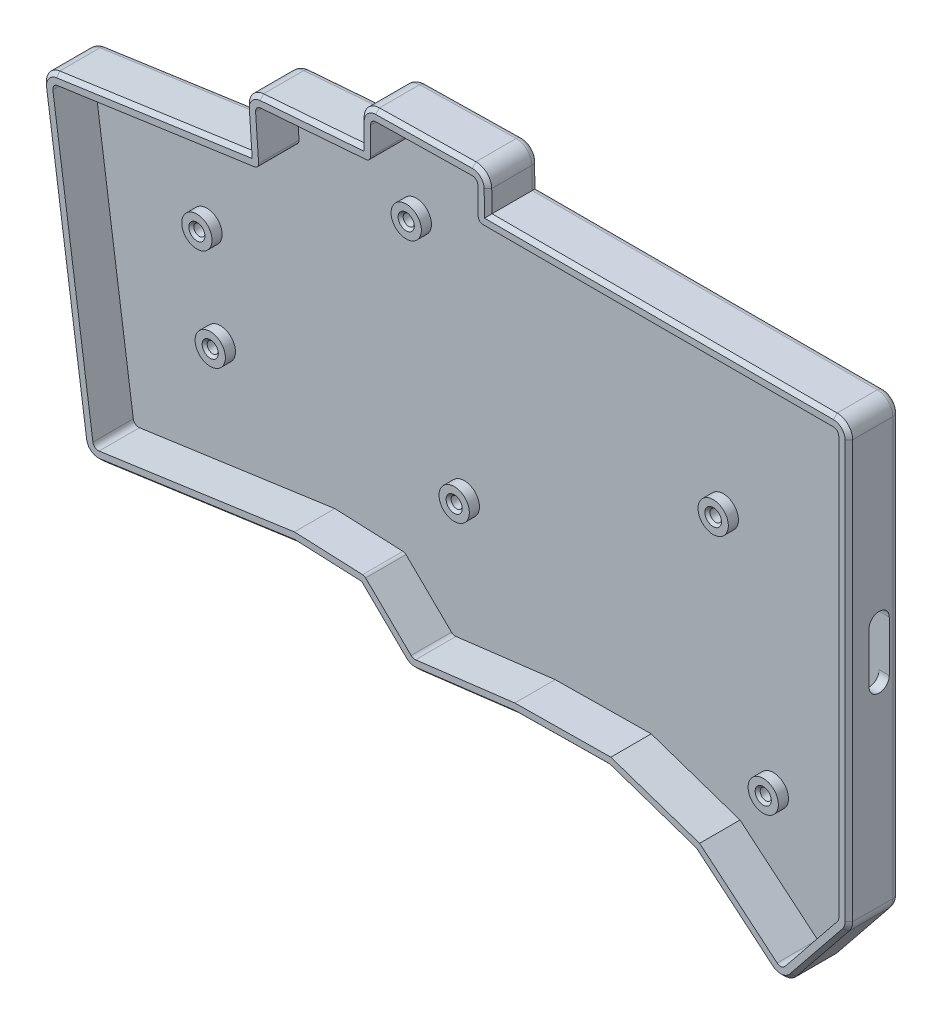
SolidWorks part; units mm, degrees
ref_plane "Front Plane" through (0, 0, 0) normal (0, 0, 1) x (1, 0, 0)
ref_plane "Top Plane" through (0, 0, 0) normal (0, 1, 0) x (1, 0, 0)
ref_plane "Right Plane" through (0, 0, 0) normal (1, 0, 0) x (0, 0, -1)
sketch "Sketch3" plane through (0, 0, 0) normal (0, 0, 1) x (1, 0, 0)
  line L0 (85.1833, 97.7805) -> (154.5968, 97.7805)
  line L1 (155.6718, 96.7055) -> (155.6718, 14.0578)
  line L2 (155.4344, 13.384) -> (144.9894, 0.4011)
  line L3 (143.4619, 0.2505) -> (128.1082, 13.0973)
  line L4 (128.1082, 13.0973) -> (143.4619, 0.2505)
  line L5 (128.1082, 13.0973) -> (110.5249, 19.0829)
  line L6 (110.5249, 19.0829) -> (91.5019, 18.8692)
  line L7 (91.5019, 18.8692) -> (71.8411, 16.4484)
  line L8 (70.9583, 16.7466) -> (61.9589, 25.5411)
  line L9 (70.9583, 16.7466) -> (61.9589, 25.5411)
  line L10 (61.3523, 25.8037) -> (47.8521, 26.3837)
  line L11 (47.8521, 26.3837) -> (9.158, 20.9127)
  line L12 (7.9428, 21.8276) -> (0.0098, 78.274)
  line L13 (0.9224, 79.4879) -> (39.9728, 85.0637)
  line L14 (40.7648, 86.0439) -> (40.1665, 94.5997)
  line L15 (41.1563, 95.7465) -> (62.0679, 97.3591)
  line L16 (62.9218, 98.2813) -> (62.9218, 103.7219)
  line L17 (63.979, 104.7967) -> (83.0927, 105.1138)
  line L18 (84.1855, 104.0536) -> (84.2584, 98.6929)
  line L19 (61.2805, 24.8059) -> (47.901, 25.3807)
  line L20 (47.901, 25.3807) -> (9.298, 19.9225)
  line L21 (6.9525, 21.6885) -> (-0.9804, 78.1349)
  line L22 (0.7811, 80.4778) -> (39.7624, 86.0438)
  line L23 (39.7624, 86.0438) -> (39.169, 94.5299)
  line L24 (41.0794, 96.7436) -> (61.9218, 98.3508)
  line L25 (61.9218, 98.3508) -> (61.9218, 103.7219)
  line L26 (63.9624, 105.7966) -> (83.0761, 106.1137)
  line L27 (85.1854, 104.0671) -> (85.2573, 98.7805)
  line L28 (85.2573, 98.7805) -> (154.5968, 98.7805)
  line L29 (156.6718, 96.7055) -> (156.6718, 14.0578)
  line L30 (156.2136, 12.7572) -> (145.7685, -0.2258)
  line L31 (142.8202, -0.5165) -> (127.6095, 12.2107)
  line L32 (127.6095, 12.2107) -> (110.3649, 18.081)
  line L33 (110.3649, 18.081) -> (91.5689, 17.8699)
  line L34 (91.5689, 17.8699) -> (71.9634, 15.4559)
  line L35 (70.2594, 16.0314) -> (61.2805, 24.8059)
  line L36 (60.8552, 23.8232) -> (47.95, 24.3777)
  line L37 (47.95, 24.3777) -> (9.438, 18.9324)
  line L38 (5.9622, 21.5493) -> (-1.9707, 77.9957)
  line L39 (0.6397, 81.4678) -> (38.6999, 86.9022)
  line L40 (38.6999, 86.9022) -> (38.1714, 94.4602)
  line L41 (41.0025, 97.7406) -> (60.9218, 99.2767)
  line L42 (60.9218, 99.2767) -> (60.9218, 103.7219)
  line L43 (63.9458, 106.7965) -> (83.0596, 107.1135)
  line L44 (86.1853, 104.0807) -> (86.2438, 99.7805)
  line L45 (86.2438, 99.7805) -> (154.5968, 99.7805)
  line L46 (157.6718, 96.7055) -> (157.6718, 14.0578)
  line L47 (156.9927, 12.1304) -> (146.5477, -0.8526)
  line L48 (142.1785, -1.2834) -> (127.1108, 11.3241)
  line L49 (127.1108, 11.3241) -> (110.2048, 17.0791)
  line L50 (110.2048, 17.0791) -> (91.6358, 16.8706)
  line L51 (91.6358, 16.8706) -> (72.0856, 14.4634)
  line L52 (69.5605, 15.3162) -> (60.8552, 23.8232)
  arc A0 (154.5968, 97.7805) -> (155.6718, 96.7055) centre (154.5968, 96.7055) cw
  arc A1 (155.6718, 14.0578) -> (155.4344, 13.384) centre (154.597, 14.0578) cw
  arc A2 (144.9894, 0.4011) -> (143.4619, 0.2505) centre (144.1518, 1.0749) cw
  arc A3 (71.8411, 16.4484) -> (70.9583, 16.7466) centre (71.7098, 17.5155) cw
  arc A4 (61.9589, 25.5411) -> (61.3523, 25.8037) centre (61.3124, 24.8796) ccw
  arc A5 (9.158, 20.9127) -> (7.9428, 21.8276) centre (9.0075, 21.9773) cw
  arc A6 (0.0098, 78.274) -> (0.9224, 79.4879) centre (1.0744, 78.4236) cw
  arc A7 (39.9728, 85.0637) -> (40.7648, 86.0439) centre (39.8421, 85.9794) ccw
  arc A8 (40.1665, 94.5997) -> (41.1563, 95.7465) centre (41.2389, 94.6747) cw
  arc A9 (62.0679, 97.3591) -> (62.9218, 98.2813) centre (61.9968, 98.2814) ccw
  arc A10 (62.9218, 103.7219) -> (63.979, 104.7967) centre (63.9968, 103.7219) cw
  arc A11 (83.0927, 105.1138) -> (84.1855, 104.0536) centre (83.1106, 104.0389) cw
  arc A12 (84.2584, 98.6929) -> (85.1833, 97.7805) centre (85.1833, 98.7055) ccw
  circle A13 centre (22.5341, 62.2507) radius 1.1001
  circle A14 centre (25.1783, 43.4356) radius 1.1001
  circle A15 centre (63.9968, 84.7054) radius 1.1001
  circle A16 centre (73.4968, 41.0054) radius 1.1001
  circle A17 centre (124.7968, 64.4055) radius 1.1454
  circle A18 centre (134.7093, 21.5464) radius 1.1001
  arc A19 (61.2805, 24.8059) -> (61.2805, 24.8059) centre (61.2805, 24.8059) ccw
  arc A20 (9.298, 19.9225) -> (6.9525, 21.6885) centre (9.0075, 21.9773) cw
  arc A21 (-0.9804, 78.1349) -> (0.7811, 80.4778) centre (1.0744, 78.4236) cw
  arc A22 (39.7624, 86.0438) -> (39.7624, 86.0438) centre (39.7624, 86.0438) ccw
  arc A23 (39.169, 94.5299) -> (41.0794, 96.7436) centre (41.2389, 94.6747) cw
  arc A24 (61.9218, 98.3508) -> (61.9218, 98.3508) centre (61.9218, 98.3508) ccw
  arc A25 (61.9218, 103.7219) -> (63.9624, 105.7966) centre (63.9968, 103.7219) cw
  arc A26 (83.0761, 106.1137) -> (85.1854, 104.0671) centre (83.1106, 104.0389) cw
  arc A27 (85.2573, 98.7805) -> (85.2573, 98.7805) centre (85.2573, 98.7805) ccw
  arc A28 (154.5968, 98.7805) -> (156.6718, 96.7055) centre (154.5968, 96.7055) cw
  arc A29 (156.6718, 14.0578) -> (156.2136, 12.7572) centre (154.597, 14.0578) cw
  arc A30 (145.7685, -0.2258) -> (142.8202, -0.5165) centre (144.1518, 1.0749) cw
  arc A31 (71.9634, 15.4559) -> (70.2594, 16.0314) centre (71.7098, 17.5155) cw
  arc A32 (9.438, 18.9324) -> (5.9622, 21.5493) centre (9.0075, 21.9773) cw
  arc A33 (-1.9707, 77.9957) -> (0.6397, 81.4678) centre (1.0744, 78.4236) cw
  arc A34 (38.6999, 86.9022) -> (38.6999, 86.9022) centre (38.6999, 86.9022) ccw
  arc A35 (38.1714, 94.4602) -> (41.0025, 97.7406) centre (41.2389, 94.6747) cw
  arc A36 (60.9218, 99.2767) -> (60.9218, 99.2767) centre (60.9218, 99.2767) ccw
  arc A37 (60.9218, 103.7219) -> (63.9458, 106.7965) centre (63.9968, 103.7219) cw
  arc A38 (83.0596, 107.1135) -> (86.1853, 104.0807) centre (83.1106, 104.0389) cw
  arc A39 (86.2438, 99.7805) -> (86.2438, 99.7805) centre (86.2438, 99.7805) ccw
  arc A40 (154.5968, 99.7805) -> (157.6718, 96.7055) centre (154.5968, 96.7055) cw
  arc A41 (157.6718, 14.0578) -> (156.9927, 12.1304) centre (154.597, 14.0578) cw
  arc A42 (146.5477, -0.8526) -> (142.1785, -1.2834) centre (144.1518, 1.0749) cw
  arc A43 (72.0856, 14.4634) -> (69.5605, 15.3162) centre (71.7098, 17.5155) cw
  arc A44 (60.8552, 23.8232) -> (60.8552, 23.8232) centre (60.8552, 23.8232) ccw
  dimension "D1" = 1
  dimension "D2" = 1
extrude "Boss-Extrude1" add sketch "Sketch3" along normal blind 2 contours A43 L51 L50 L49 L48 A42 L47 A41 L46 A40 L45 L44 A38 L43 A37 L42 L41 A35 L40 L39 A33 L38 A32 L37 L36 L52 L34 A31 L35 L19 L20 A20 L21 A21 L22 L23 A23 L24 L25 A25 L26 A26 L27 L28 A28 L29 A29 L30 A30 L31 | A31 L34 L33 L32 L31 A30 L30 A29 L29 A28 L28 L27 A26 L26 A25 L25 L24 A23 L23 L22 A21 L21 A20 L20 L19 L35 L18 A12 L0 A0 L1 A1 L2 A2 L3 L5 L6 L7 A3 L8 A4 L10 L11 A5 L12 A6 L13 A7 L14 A8 | A12 L18 A11 L17 A10 L16 A9 L15 A8 L14 A7 L13 A6 L12 A5 L11 L10 A4 L8 A3 L7 L6 L5 L3 A2 L2 A1 L1 A0 L0 A18 A17 A16 A15 A14 A13 | A13 | A14 | A15 | A16 | A17 | A18
sketch "Sketch4" plane through (0, 0, 0) normal (0, 0, 1) x (1, 0, 0)
  line L0 (85.1833, 97.7805) -> (154.5968, 97.7805)
  line L1 (155.6718, 96.7055) -> (155.6718, 14.0578)
  line L2 (155.4344, 13.384) -> (144.9894, 0.4011)
  line L3 (143.4619, 0.2505) -> (128.1082, 13.0973)
  line L4 (128.1082, 13.0973) -> (143.4619, 0.2505)
  line L5 (128.1082, 13.0973) -> (110.5249, 19.0829)
  line L6 (110.5249, 19.0829) -> (91.5019, 18.8692)
  line L7 (91.5019, 18.8692) -> (71.8411, 16.4484)
  line L8 (70.9583, 16.7466) -> (61.9589, 25.5411)
  line L9 (70.9583, 16.7466) -> (61.9589, 25.5411)
  line L10 (61.3523, 25.8037) -> (47.8521, 26.3837)
  line L11 (47.8521, 26.3837) -> (9.158, 20.9127)
  line L12 (7.9428, 21.8276) -> (0.0098, 78.274)
  line L13 (0.9224, 79.4879) -> (39.9728, 85.0637)
  line L14 (40.7648, 86.0439) -> (40.1665, 94.5997)
  line L15 (41.1563, 95.7465) -> (62.0679, 97.3591)
  line L16 (62.9218, 98.2813) -> (62.9218, 103.7219)
  line L17 (63.979, 104.7967) -> (83.0927, 105.1138)
  line L18 (84.1855, 104.0536) -> (84.2584, 98.6929)
  line L19 (61.2805, 24.8059) -> (47.901, 25.3807)
  line L20 (47.901, 25.3807) -> (9.298, 19.9225)
  line L21 (6.9525, 21.6885) -> (-0.9804, 78.1349)
  line L22 (0.7811, 80.4778) -> (39.7624, 86.0438)
  line L23 (39.7624, 86.0438) -> (39.169, 94.5299)
  line L24 (41.0794, 96.7436) -> (61.9218, 98.3508)
  line L25 (61.9218, 98.3508) -> (61.9218, 103.7219)
  line L26 (63.9624, 105.7966) -> (83.0761, 106.1137)
  line L27 (85.1854, 104.0671) -> (85.2573, 98.7805)
  line L28 (85.2573, 98.7805) -> (154.5968, 98.7805)
  line L29 (156.6718, 96.7055) -> (156.6718, 14.0578)
  line L30 (156.2136, 12.7572) -> (145.7685, -0.2258)
  line L31 (142.8202, -0.5165) -> (127.6095, 12.2107)
  line L32 (127.6095, 12.2107) -> (110.3649, 18.081)
  line L33 (110.3649, 18.081) -> (91.5689, 17.8699)
  line L34 (91.5689, 17.8699) -> (71.9634, 15.4559)
  line L35 (70.2594, 16.0314) -> (61.2805, 24.8059)
  line L36 (60.8552, 23.8232) -> (47.95, 24.3777)
  line L37 (47.95, 24.3777) -> (9.438, 18.9324)
  line L38 (5.9622, 21.5493) -> (-1.9707, 77.9957)
  line L39 (0.6397, 81.4678) -> (38.6999, 86.9022)
  line L40 (38.6999, 86.9022) -> (38.1714, 94.4602)
  line L41 (41.0025, 97.7406) -> (60.9218, 99.2767)
  line L42 (60.9218, 99.2767) -> (60.9218, 103.7219)
  line L43 (63.9458, 106.7965) -> (83.0596, 107.1135)
  line L44 (86.1853, 104.0807) -> (86.2438, 99.7805)
  line L45 (86.2438, 99.7805) -> (154.5968, 99.7805)
  line L46 (157.6718, 96.7055) -> (157.6718, 14.0578)
  line L47 (156.9927, 12.1304) -> (146.5477, -0.8526)
  line L48 (142.1785, -1.2834) -> (127.1108, 11.3241)
  line L49 (127.1108, 11.3241) -> (110.2048, 17.0791)
  line L50 (110.2048, 17.0791) -> (91.6358, 16.8706)
  line L51 (91.6358, 16.8706) -> (72.0856, 14.4634)
  line L52 (69.5605, 15.3162) -> (60.8552, 23.8232)
  arc A0 (154.5968, 97.7805) -> (155.6718, 96.7055) centre (154.5968, 96.7055) cw
  arc A1 (155.6718, 14.0578) -> (155.4344, 13.384) centre (154.597, 14.0578) cw
  arc A2 (144.9894, 0.4011) -> (143.4619, 0.2505) centre (144.1518, 1.0749) cw
  arc A3 (71.8411, 16.4484) -> (70.9583, 16.7466) centre (71.7098, 17.5155) cw
  arc A4 (61.9589, 25.5411) -> (61.3523, 25.8037) centre (61.3124, 24.8796) ccw
  arc A5 (9.158, 20.9127) -> (7.9428, 21.8276) centre (9.0075, 21.9773) cw
  arc A6 (0.0098, 78.274) -> (0.9224, 79.4879) centre (1.0744, 78.4236) cw
  arc A7 (39.9728, 85.0637) -> (40.7648, 86.0439) centre (39.8421, 85.9794) ccw
  arc A8 (40.1665, 94.5997) -> (41.1563, 95.7465) centre (41.2389, 94.6747) cw
  arc A9 (62.0679, 97.3591) -> (62.9218, 98.2813) centre (61.9968, 98.2814) ccw
  arc A10 (62.9218, 103.7219) -> (63.979, 104.7967) centre (63.9968, 103.7219) cw
  arc A11 (83.0927, 105.1138) -> (84.1855, 104.0536) centre (83.1106, 104.0389) cw
  arc A12 (84.2584, 98.6929) -> (85.1833, 97.7805) centre (85.1833, 98.7055) ccw
  circle A13 centre (22.5341, 62.2507) radius 1.1001
  circle A14 centre (25.1783, 43.4356) radius 1.1001
  circle A15 centre (63.9968, 84.7054) radius 1.1001
  circle A16 centre (73.4968, 41.0054) radius 1.1001
  circle A17 centre (124.7968, 64.4055) radius 1.1454
  circle A18 centre (134.7093, 21.5464) radius 1.1001
  arc A19 (61.2805, 24.8059) -> (61.2805, 24.8059) centre (61.2805, 24.8059) ccw
  arc A20 (9.298, 19.9225) -> (6.9525, 21.6885) centre (9.0075, 21.9773) cw
  arc A21 (-0.9804, 78.1349) -> (0.7811, 80.4778) centre (1.0744, 78.4236) cw
  arc A22 (39.7624, 86.0438) -> (39.7624, 86.0438) centre (39.7624, 86.0438) ccw
  arc A23 (39.169, 94.5299) -> (41.0794, 96.7436) centre (41.2389, 94.6747) cw
  arc A24 (61.9218, 98.3508) -> (61.9218, 98.3508) centre (61.9218, 98.3508) ccw
  arc A25 (61.9218, 103.7219) -> (63.9624, 105.7966) centre (63.9968, 103.7219) cw
  arc A26 (83.0761, 106.1137) -> (85.1854, 104.0671) centre (83.1106, 104.0389) cw
  arc A27 (85.2573, 98.7805) -> (85.2573, 98.7805) centre (85.2573, 98.7805) ccw
  arc A28 (154.5968, 98.7805) -> (156.6718, 96.7055) centre (154.5968, 96.7055) cw
  arc A29 (156.6718, 14.0578) -> (156.2136, 12.7572) centre (154.597, 14.0578) cw
  arc A30 (145.7685, -0.2258) -> (142.8202, -0.5165) centre (144.1518, 1.0749) cw
  arc A31 (71.9634, 15.4559) -> (70.2594, 16.0314) centre (71.7098, 17.5155) cw
  arc A32 (9.438, 18.9324) -> (5.9622, 21.5493) centre (9.0075, 21.9773) cw
  arc A33 (-1.9707, 77.9957) -> (0.6397, 81.4678) centre (1.0744, 78.4236) cw
  arc A34 (38.6999, 86.9022) -> (38.6999, 86.9022) centre (38.6999, 86.9022) ccw
  arc A35 (38.1714, 94.4602) -> (41.0025, 97.7406) centre (41.2389, 94.6747) cw
  arc A36 (60.9218, 99.2767) -> (60.9218, 99.2767) centre (60.9218, 99.2767) ccw
  arc A37 (60.9218, 103.7219) -> (63.9458, 106.7965) centre (63.9968, 103.7219) cw
  arc A38 (83.0596, 107.1135) -> (86.1853, 104.0807) centre (83.1106, 104.0389) cw
  arc A39 (86.2438, 99.7805) -> (86.2438, 99.7805) centre (86.2438, 99.7805) ccw
  arc A40 (154.5968, 99.7805) -> (157.6718, 96.7055) centre (154.5968, 96.7055) cw
  arc A41 (157.6718, 14.0578) -> (156.9927, 12.1304) centre (154.597, 14.0578) cw
  arc A42 (146.5477, -0.8526) -> (142.1785, -1.2834) centre (144.1518, 1.0749) cw
  arc A43 (72.0856, 14.4634) -> (69.5605, 15.3162) centre (71.7098, 17.5155) cw
  arc A44 (60.8552, 23.8232) -> (60.8552, 23.8232) centre (60.8552, 23.8232) ccw
  dimension "D1" = 1
  dimension "D2" = 1
extrude "Boss-Extrude2" add sketch "Sketch4" along normal blind 10 contours A43 L51 L50 L49 L48 A42 L47 A41 L46 A40 L45 L44 A38 L43 A37 L42 L41 A35 L40 L39 A33 L38 A32 L37 L36 L52 L34 A31 L35 L19 L20 A20 L21 A21 L22 L23 A23 L24 L25 A25 L26 A26 L27 L28 A28 L29 A29 L30 A30 L31 | A31 L34 L33 L32 L31 A30 L30 A29 L29 A28 L28 L27 A26 L26 A25 L25 L24 A23 L23 L22 A21 L21 A20 L20 L19 L35 L18 A12 L0 A0 L1 A1 L2 A2 L3 L5 L6 L7 A3 L8 A4 L10 L11 A5 L12 A6 L13 A7 L14 A8
sketch "Sketch7" plane through (0, 0, 0) normal (0, 0, 1) x (1, 0, 0)
  circle A0 centre (25.1783, 43.4356) radius 3
  circle A1 centre (22.5341, 62.2507) radius 3
  circle A2 centre (63.9968, 84.7054) radius 3
  circle A3 centre (73.4968, 41.0054) radius 3
  circle A4 centre (124.7968, 64.4055) radius 3
  circle A5 centre (134.7093, 21.5464) radius 3
  circle A13 centre (22.5341, 62.2507) radius 1.1001
  circle A14 centre (25.1783, 43.4356) radius 1.1001
  circle A15 centre (63.9968, 84.7054) radius 1.1001
  circle A16 centre (73.4968, 41.0054) radius 1.1001
  circle A17 centre (124.7968, 64.4055) radius 1.1454
  circle A18 centre (134.7093, 21.5464) radius 1.1001
  dimension "D1" = 6
  dimension "D2" = 6
  dimension "D3" = 6
  dimension "D4" = 6
  dimension "D5" = 6
  dimension "D6" = 6
extrude "Boss-Extrude3" add sketch "Sketch7" along normal blind 4
sketch "Sketch8" plane through (157.6718, 0, 0) normal (1, 0, 0) x (0, 0, -1)
  line L0 (0, 96.7055) -> (0, 14.0578) construction
  line L5 (-4, 62.6695) -> (-4, 52.6695) construction
  line L6 (-2, 62.6695) -> (-2, 52.6695)
  line L7 (-6, 62.6695) -> (-6, 52.6695)
  line L8 (-10, 96.7055) -> (0, 96.7055) construction
  arc A0 (-2, 62.6695) -> (-6, 62.6695) centre (-4, 62.6695) ccw
  arc A1 (-6, 52.6695) -> (-2, 52.6695) centre (-4, 52.6695) ccw
  point P8 (-4, 57.6695)
  dimension "D1" = 10
  dimension "D2" = 2
  dimension "D3" = 34.036
  dimension "D4" = 2
extrude "Cut-Extrude1" cut sketch "Sketch8" against normal blind 3
fillet "Fillet2" radius 1.3 26 edges at (81.8607, 15.667, 0) (100.9203, 16.9749, 0) (118.6578, 14.2016, 0) (134.6446, 5.0203, 0) (144.4535, -1.9852, 0) (151.7702, 5.6389, 0) (157.4971, 13.036, 0) (157.6718, 55.3816, 0) (156.7712, 98.8798, 0) (120.4203, 99.7805, 0) (86.2145, 101.9306, 0) (85.2519, 106.2459, 0) (73.5027, 106.955, 0) (61.8045, 105.8781, 0) (60.9218, 101.4993, 0) (50.9622, 98.5086, 0) (38.911, 96.6838, 0) (38.4356, 90.6812, 0) (54.4026, 24.1004, 0) (65.2079, 19.5697, 0) (70.7258, 14.602, 0) (19.6698, 84.185, 0) (-1.3835, 80.2715, 0) (1.9958, 49.7725, 0) (7.1578, 19.5206, 0) (28.694, 21.655, 0)
chamfer "Chamfer1" distance 0.75 angle 45 26 edges at (65.2079, 19.5697, 10) (54.4026, 24.1004, 10) (70.7258, 14.602, 10) (81.8607, 15.667, 10) (100.9203, 16.9749, 10) (118.6578, 14.2016, 10) (134.6446, 5.0203, 10) (144.4535, -1.9852, 10) (151.7702, 5.6389, 10) (157.4971, 13.036, 10) (157.6718, 55.3816, 10) (156.7712, 98.8798, 10) (120.4203, 99.7805, 10) (86.2145, 101.9306, 10) (85.2519, 106.2459, 10) (73.5027, 106.955, 10) (61.8045, 105.8781, 10) (60.9218, 101.4993, 10) (50.9622, 98.5086, 10) (38.911, 96.6838, 10) (38.4356, 90.6812, 10) (19.6698, 84.185, 10) (-1.3835, 80.2715, 10) (1.9958, 49.7725, 10) (7.1578, 19.5206, 10) (28.694, 21.655, 10)
chamfer "Chamfer2" distance 0.5 angle 45 6 edges at (26.2784, 43.4356, 4) (74.5969, 41.0054, 4) (135.8094, 21.5464, 4) (125.9422, 64.4055, 4) (65.0969, 84.7054, 4) (23.6341, 62.2507, 4)
